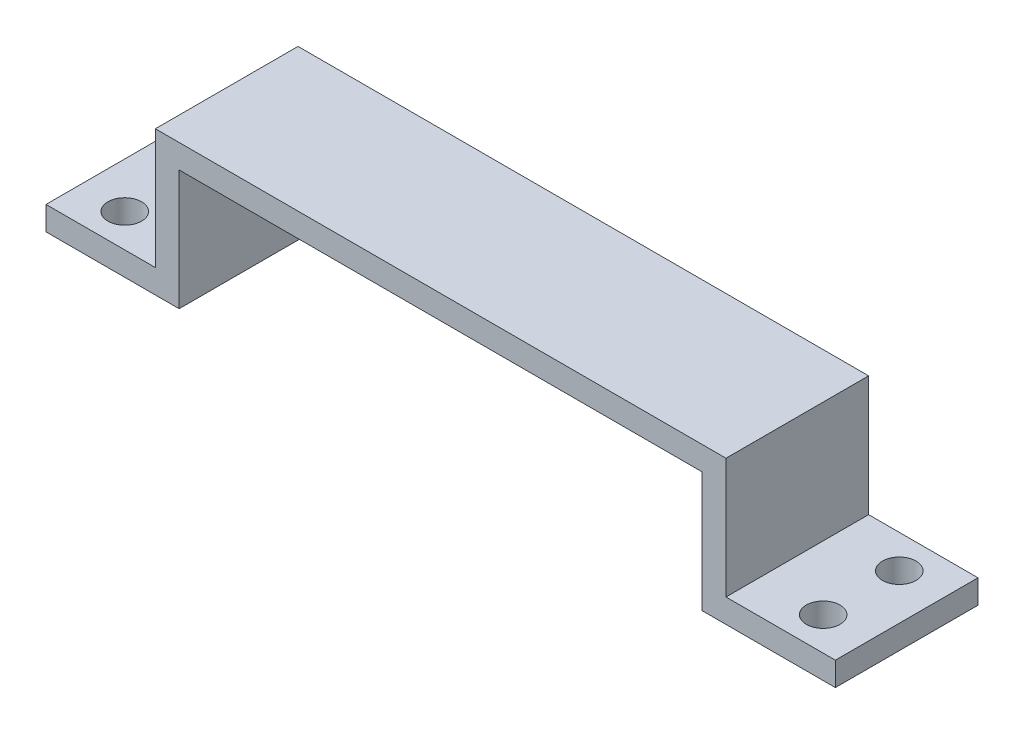
SolidWorks part; units mm, degrees
ref_plane "Front Plane" through (0, 0, 0) normal (0, 0, 1) x (1, 0, 0)
ref_plane "Top Plane" through (0, 0, 0) normal (0, 1, 0) x (1, 0, 0)
ref_plane "Right Plane" through (0, 0, 0) normal (1, 0, 0) x (0, 0, -1)
sketch "Sketch1" plane through (0, 0, 0) normal (0, 0, 1) x (1, 0, 0)
  line L0 (0, 0) -> (-38.1, 0)
  line L1 (-38.1, 0) -> (-38.1, -16.0528)
  line L2 (-38.1, -16.0528) -> (-52.705, -16.0528)
  line L3 (-52.705, -16.0528) -> (-52.705, -19.2278)
  line L4 (-52.705, -19.2278) -> (-34.925, -19.2278)
  line L5 (-34.925, -19.2278) -> (-34.925, -3.175)
  line L6 (-34.925, -3.175) -> (0, -3.175)
  line L7 (0, -3.175) -> (0, 0)
  line L8 (-34.925, -3.175) -> (-38.1, -3.175) construction
  dimension "D1" = 3.175
  dimension "D2" = 17.78
  dimension "D3" = 16.0528
  dimension "D4" = 34.925
extrude "Extrude1" add sketch "Sketch1" along normal blind 19.05
sketch "Sketch2" plane through (0, -16.0528, 0) normal (0, 1, 0) x (1, 0, 0)
  line L0 (-52.705, -9.525) -> (-46.6344, -9.525) construction
  line L1 (-52.705, -19.05) -> (-52.705, 0) construction
  line L2 (-46.6344, -9.525) -> (-46.6344, -4.445) construction
  line L3 (-46.6344, -9.525) -> (-46.6344, -14.605) construction
  line L4 (0, -55) -> (0, 55) construction
  dimension "D1" = 10.16
  dimension "D2" = 46.6344
hole_wizard "#8 Clearance Hole1" positions "3DSketch1" profile "Sketch3" hole size "#8" standard "Ansi Inch" end condition through all
sketch3d "3DSketch1"
  point P0 (-46.6344, -16.0528, 4.445)
  point P3 (-46.6344, -16.0528, 14.605)
sketch "Sketch3" plane through (-46.6344, -16.0528, 4.445) normal (1, 0, 0) x (0, 0, 1)
  line L0 (0, 0) -> (0, 3.175)
  line L1 (0, 3.175) -> (2.2479, 3.175)
  line L2 (2.2479, 3.175) -> (2.2479, 0)
  line L5 (2.2479, 0) -> (0, 0)
  line L11 (0, -6.35) -> (0, 107.95) construction
  dimension "Thru Hole Dia." = 4.4958
  dimension "Thru Hole Depth" = 3.175
mirror "Mirror1" about plane through (0, 0, 0) normal (1, 0, 0) of "#8 Clearance Hole1", "Extrude1"
